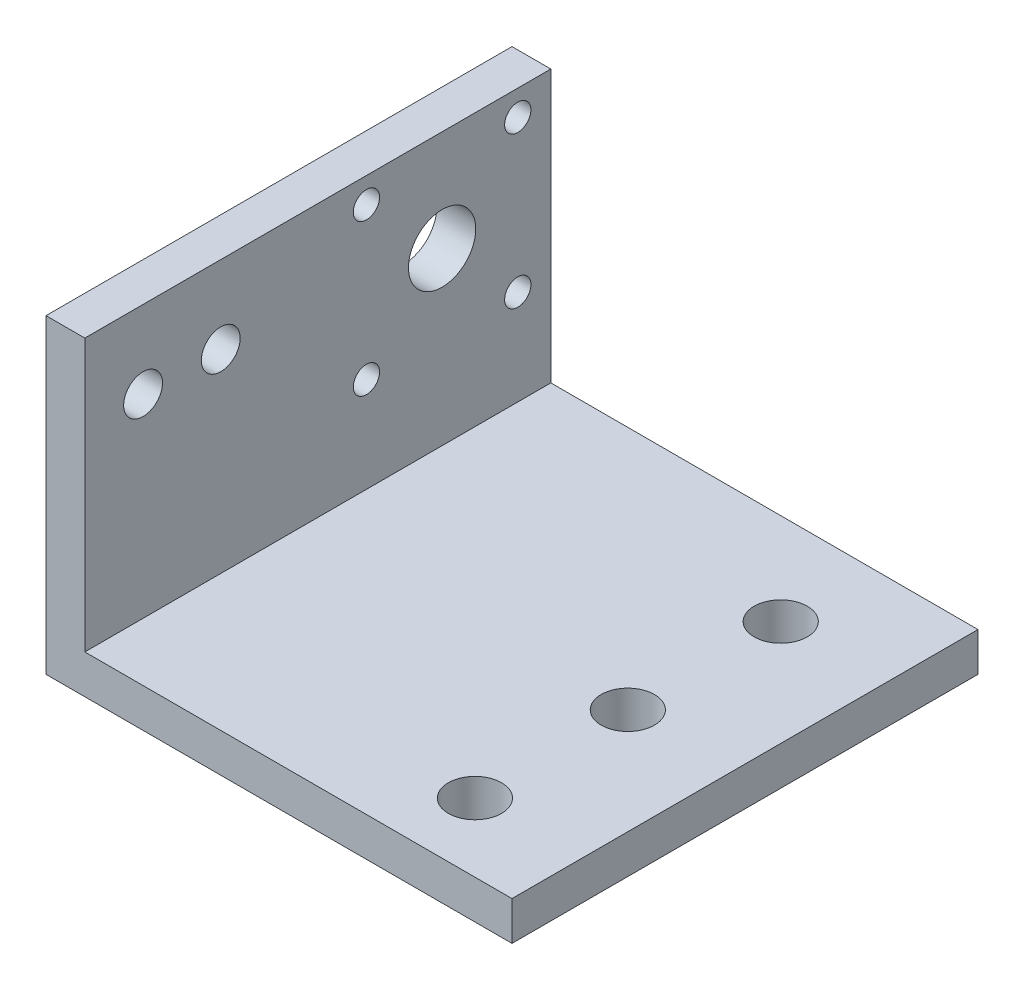
SolidWorks part; units mm, degrees
material "6061 Alloy"
ref_plane "Front Plane" through (0, 0, 0) normal (0, 0, 1) x (1, 0, 0)
ref_plane "Top Plane" through (0, 0, 0) normal (0, 1, 0) x (1, 0, 0)
ref_plane "Right Plane" through (0, 0, 0) normal (1, 0, 0) x (0, 0, -1)
sketch "Sketch1" plane through (0, 0, 0) normal (0, 0, 1) x (1, 0, 0)
  line L0 (-35.999, 18.8304) -> (-35.999, -25.6196)
  line L1 (-35.999, -25.6196) -> (33.851, -25.6196)
  line L2 (-42.349, 18.8304) -> (-42.349, -31.9696)
  line L3 (-42.349, -31.9696) -> (33.851, -31.9696)
  line L4 (-42.349, 18.8304) -> (-35.999, 18.8304)
  line L5 (33.851, -25.6196) -> (33.851, -31.9696)
  dimension "D2" = 50.8
  dimension "D3" = 76.2
  dimension "D1" = 6.35
extrude "Boss-Extrude1" add sketch "Sketch1" along normal blind 76.2
sketch "Sketch2" plane through (-35.999, 0, 0) normal (1, 0, 0) x (0, 0, -1)
  line L0 (-76.2, -25.6196) -> (0, -25.6196) construction
  line L1 (0, -25.6196) -> (0, 18.8304) construction
  circle A0 centre (-17.78, 2.3204) radius 5.5
  dimension "D1" = 27.94
  dimension "D2" = 17.78
  dimension "D3" = 11
hole_wizard "M4 Clearance Hole1" positions "Sketch5" profile "Sketch3" hole size "M4" standard "ANSI Metric" end condition up to next
sketch "Sketch5" plane through (-35.999, 0, 0) normal (1, 0, 0) x (0, 0, -1)
  line L2 (-30.1548, -10.0544) -> (-5.4052, -10.0544)
  line L3 (-30.1548, -10.0544) -> (-30.1548, 14.6952)
  line L4 (-30.1548, 14.6952) -> (-5.4052, 14.6952)
  line L5 (-5.4052, -10.0544) -> (-5.4052, 14.6952)
  line L6 (-30.1548, -10.0544) -> (-5.4052, 14.6952) construction
  line L7 (-30.1548, 14.6952) -> (-5.4052, -10.0544) construction
  circle A1 centre (-17.78, 2.3204) radius 17.5006
  point P0 (-30.1548, 14.6952)
  point P2 (-30.1548, -10.0544)
  point P4 (-5.4052, -10.0544)
  point P6 (-5.4052, 14.6952)
  dimension "D1" = 35.0012
sketch "Sketch3" plane through (-35.999, 14.6952, 30.1548) normal (0, 1, 0) x (0, 0, -1)
  line L0 (0, 0) -> (0, 6.35)
  line L1 (0, 6.35) -> (2.15, 6.35)
  line L2 (2.15, 6.35) -> (2.15, 0)
  line L5 (2.15, 0) -> (0, 0)
  line L11 (0, -6.35) -> (0, 107.95) construction
  dimension "Thru Hole Dia." = 4.3
  dimension "Thru Hole Depth" = 6.35
extrude "Cut-Extrude1" cut sketch "Sketch2" against normal blind 8.636 contours A0
sketch "Sketch6" plane through (0, -31.9696, 0) normal (0, -1, 0) x (1, 0, 0)
  line L2 (33.851, 76.2) -> (33.851, 0) construction
  line L3 (-42.349, 38.1) -> (33.851, 38.1) construction
  line L4 (-42.349, 76.2) -> (-42.349, 0) construction
  circle A0 centre (16.5913, 65) radius 4.35
  circle A1 centre (16.5913, 15) radius 4.35
  circle A3 centre (16.5913, 40) radius 4.35
  circle A6 centre (16.5913, 15) radius 4.35 construction
  circle A8 centre (16.5913, 40) radius 4.35 construction
  circle A9 centre (16.5913, 65) radius 4.35 construction
  dimension "D1" = 8.7
  dimension "D2" = 8.7
  dimension "D4" = 8.7
extrude "Cut-Extrude2" cut sketch "Sketch6" against normal blind 13.97
sketch "Sketch7" plane through (-42.349, 0, 0) normal (-1, 0, 0) x (0, 0, 1)
  line L0 (76.2, -31.9696) -> (0, -31.9696) construction
  line L1 (76.2, 18.8304) -> (76.2, -31.9696) construction
  circle A0 centre (53.975, 6.1304) radius 3.175
  circle A1 centre (66.675, 6.1304) radius 3.175
  dimension "D3" = 6.35
  dimension "D4" = 9.525
  dimension "D1" = 38.1
  dimension "D2" = 38.1
  dimension "D5" = 22.225
extrude "Cut-Extrude3" cut sketch "Sketch7" against normal up to next
